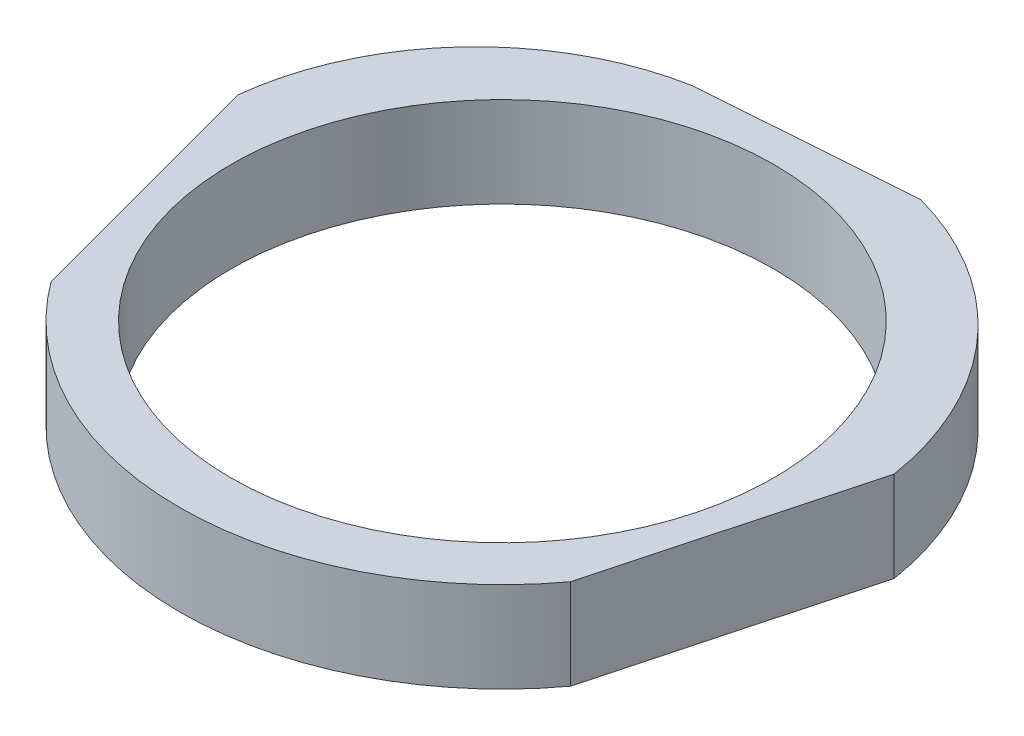
SolidWorks part; units mm, degrees
ref_plane "Front Plane" through (0, 0, 0) normal (0, 0, 1) x (1, 0, 0)
ref_plane "Top Plane" through (0, 0, 0) normal (0, 1, 0) x (1, 0, 0)
ref_plane "Right Plane" through (0, 0, 0) normal (1, 0, 0) x (0, 0, -1)
sketch "Sketch1" plane through (0, 0, 0) normal (0, 1, 0) x (1, 0, 0)
  line L0 (-12.7974, -6.35) -> (-4.0429, -6.35) construction
  line L1 (-8.6133, -6.35) -> (-10.8834, 2.105)
  line L2 (8.6133, -6.35) -> (10.8834, 2.105)
  line L3 (-8.6133, 9.5483) -> (8.6133, 10.803) construction
  line L4 (-3.5909, 9.9141) -> (3.4431, 10.4265)
  circle A0 centre (0, 0) radius 9
  arc A1 (8.6133, -6.35) -> (-8.6133, -6.35) centre (0, 0) cw
  arc A2 (-10.8834, 2.105) -> (-3.5909, 9.9141) centre (-2.0025, 1.1212) cw
  arc A3 (3.4431, 10.4265) -> (10.8834, 2.105) centre (0.7145, 0.4999) cw
  point P5 (-8.4202, -6.35)
  dimension "D1" = 18
  dimension "D2" = 6.35
extrude "Boss-Extrude1" add sketch "Sketch1" along normal mid plane 3
